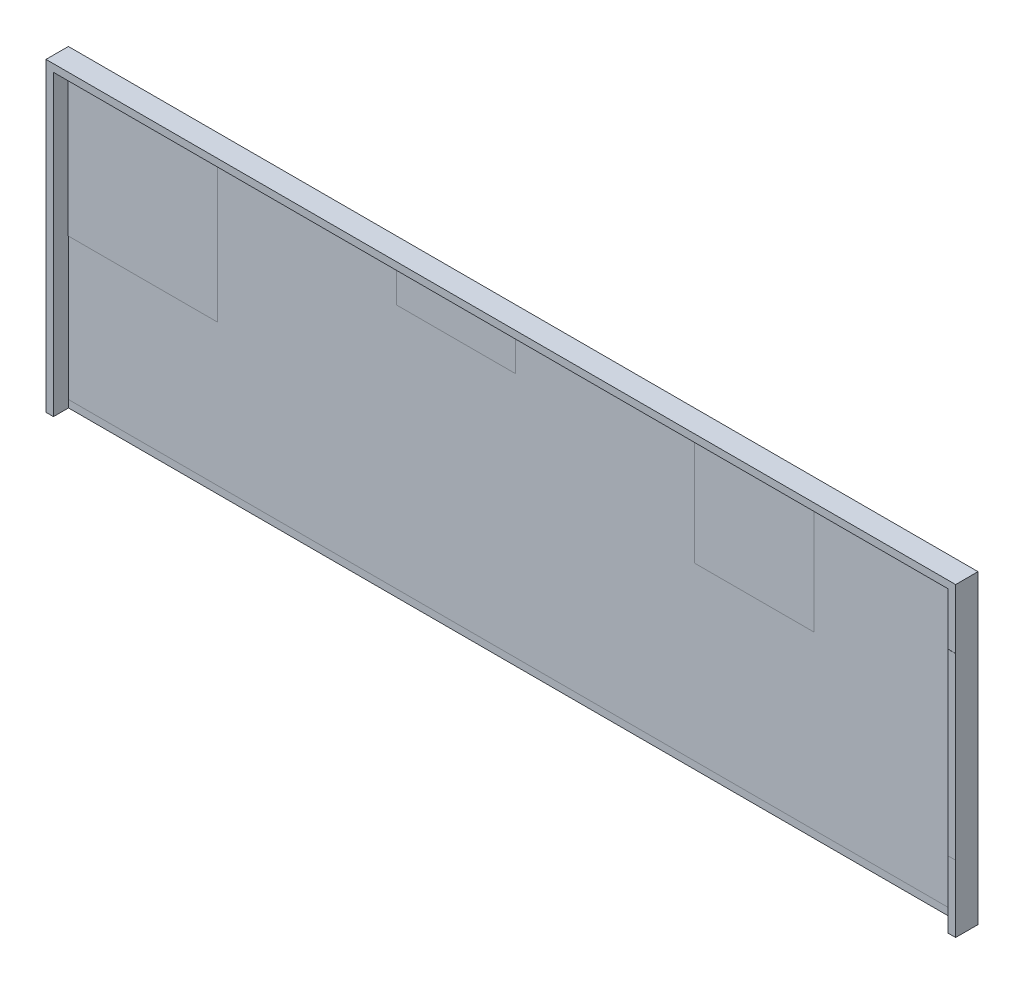
SolidWorks part; units mm, degrees
material "Teak"
ref_plane "Front Plane" through (0, 0, 0) normal (0, 0, 1) x (1, 0, 0)
ref_plane "Top Plane" through (0, 0, 0) normal (0, 1, 0) x (1, 0, 0)
ref_plane "Right Plane" through (0, 0, 0) normal (1, 0, 0) x (0, 0, -1)
sketch "Sketch1" plane through (0, 0, 0) normal (0, 0, 1) x (1, 0, 0)
  line L1 (-2432.4324, 1128.3784) -> (3667.5676, 1128.3784)
  line L2 (-2432.4324, 1128.3784) -> (-2432.4324, -921.6216)
  line L3 (-2432.4324, -921.6216) -> (3667.5676, -921.6216)
  line L4 (3667.5676, 1128.3784) -> (3667.5676, -921.6216)
  dimension "D1" = 6100
  dimension "D2" = 2050
extrude "Boss-Extrude1" add sketch "Sketch1" along normal blind 150
shell "Shell1" thickness 50
sketch "Sketch2" plane through (0, 0, 50) normal (0, 0, 1) x (1, 0, 0)
  line L1 (-2382.4324, 1078.3784) -> (-1382.4324, 1078.3784)
  line L2 (-2382.4324, 1078.3784) -> (-2382.4324, 78.3784)
  line L3 (-2382.4324, 78.3784) -> (-1382.4324, 78.3784)
  line L4 (-1382.4324, 1078.3784) -> (-1382.4324, 78.3784)
  dimension "D1" = 1000
  dimension "D2" = 1000
extrude "Boss-Extrude2" add sketch "Sketch2" along normal blind 1 contours L3 L4 L1 L2
sketch "Sketch3" plane through (0, 0, 50) normal (0, 0, 1) x (1, 0, 0)
  line L0 (3617.5676, 1078.3784) -> (-1382.4324, 1078.3784) construction
  line L1 (1817.5676, 1078.3784) -> (2617.5676, 1078.3784)
  line L2 (1817.5676, 1078.3784) -> (1817.5676, 278.3784)
  line L3 (1817.5676, 278.3784) -> (2617.5676, 278.3784)
  line L4 (2617.5676, 1078.3784) -> (2617.5676, 278.3784)
  line L5 (3617.5676, -871.6216) -> (3617.5676, 1078.3784) construction
  dimension "D1" = 800
  dimension "D2" = 800
  dimension "D3" = 1000
extrude "Boss-Extrude3" add sketch "Sketch3" along normal blind 1
sketch "Sketch4" plane through (0, 0, 50) normal (0, 0, 1) x (1, 0, 0)
  line L0 (1817.5676, 1078.3784) -> (-1382.4324, 1078.3784) construction
  line L1 (-182.4324, 1078.3784) -> (617.5676, 1078.3784)
  line L2 (-182.4324, 1078.3784) -> (-182.4324, 778.3784)
  line L3 (-182.4324, 778.3784) -> (617.5676, 778.3784)
  line L4 (617.5676, 1078.3784) -> (617.5676, 778.3784)
  line L5 (-1382.4324, 1078.3784) -> (-1382.4324, 78.3784) construction
  dimension "D1" = 800
  dimension "D2" = 300
  dimension "D3" = 1200
extrude "Boss-Extrude4" add sketch "Sketch4" along normal blind 1
sketch "Sketch5" plane through (0, 0, 150) normal (0, 0, 1) x (1, 0, 0)
  line L0 (3617.5676, -871.6216) -> (3617.5676, 1078.3784) construction
  line L1 (3617.5676, 728.3784) -> (3667.5676, 728.3784)
  line L2 (3617.5676, 728.3784) -> (3617.5676, -471.6216)
  line L3 (3617.5676, -471.6216) -> (3667.5676, -471.6216)
  line L4 (3667.5676, 728.3784) -> (3667.5676, -471.6216)
  line L5 (3667.5676, -921.6216) -> (3667.5676, 1128.3784) construction
  line L6 (3617.5676, 1078.3784) -> (2617.5676, 1078.3784) construction
  line L7 (-2432.4324, -921.6216) -> (3667.5676, -921.6216) construction
  dimension "D1" = 350
  dimension "D2" = 450
extrude "Boss-Extrude5" add sketch "Sketch5" along normal blind 1
sketch "Sketch6" plane through (0, 0, 150) normal (0, 0, 1) x (1, 0, 0)
  line L0 (-2432.4324, -921.6216) -> (3667.5676, -921.6216) construction
  line L1 (-2382.4324, -871.6216) -> (3617.5676, -871.6216)
  line L2 (-2382.4324, -871.6216) -> (-2382.4324, -921.6216)
  line L3 (-2382.4324, -921.6216) -> (3617.5676, -921.6216)
  line L4 (3617.5676, -871.6216) -> (3617.5676, -921.6216)
extrude "Cut-Extrude1" cut sketch "Sketch6" against normal blind 101
